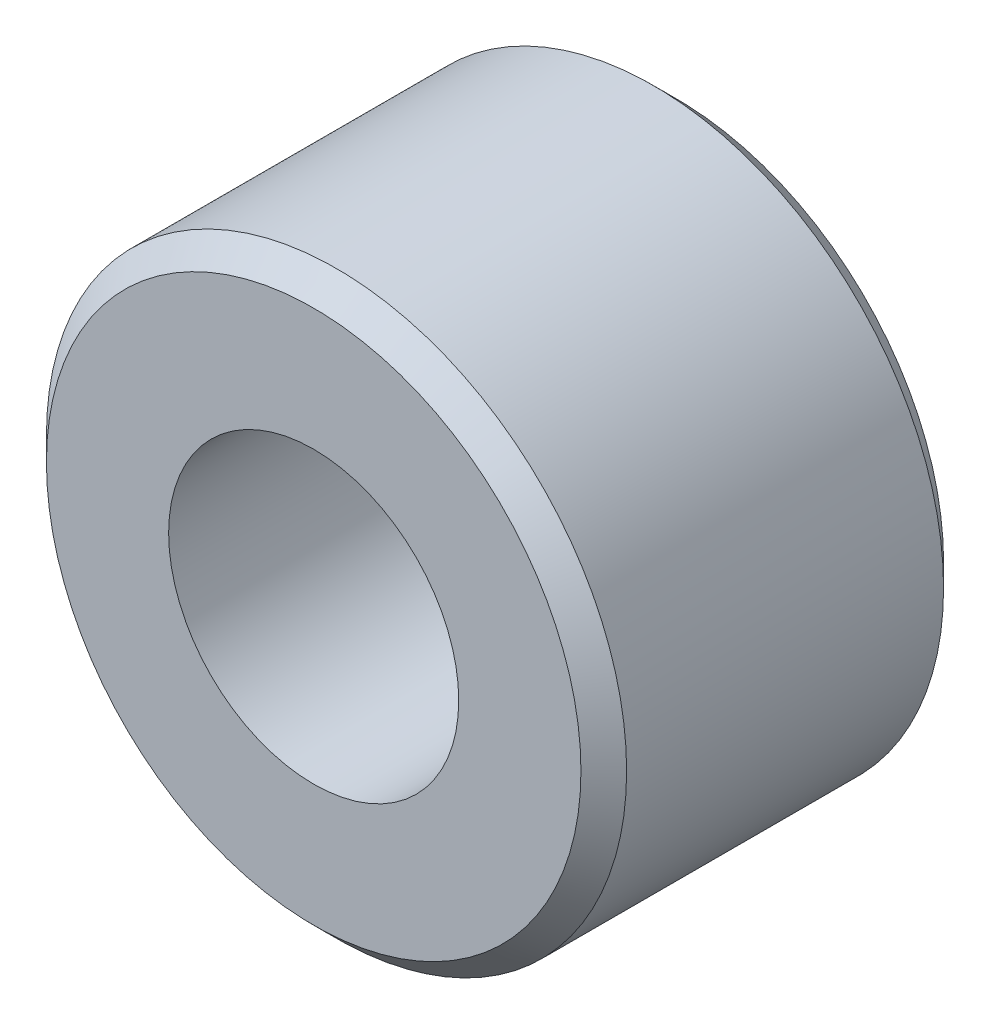
SolidWorks part; units mm, degrees
material "SAE 660 bearing bronze"
ref_plane "Front Plane" through (0, 0, 0) normal (1, 0, 0) x (0, 1, 0)
ref_plane "Top Plane" through (0, 0, 0) normal (0, 0, 1) x (0, 1, 0)
ref_plane "Right Plane" through (0, 0, 0) normal (0, 1, 0) x (-1, 0, 0)
sketch "Sketch1" plane through (0, 0, 0) normal (0, 0, 1) x (0, 1, 0)
  circle A0 centre (0, 0) radius 25.4
  circle A1 centre (0, 0) radius 12.7
  dimension "D1" = 50.8
  dimension "D2" = 25.4
extrude "Boss-Extrude1" add sketch "Sketch1" along normal blind 31.75 contours A0 A1
chamfer "Chamfer1" distance 2 angle 45 2 edges at (25.4, 0, 0) (25.4, 0, 31.75)
